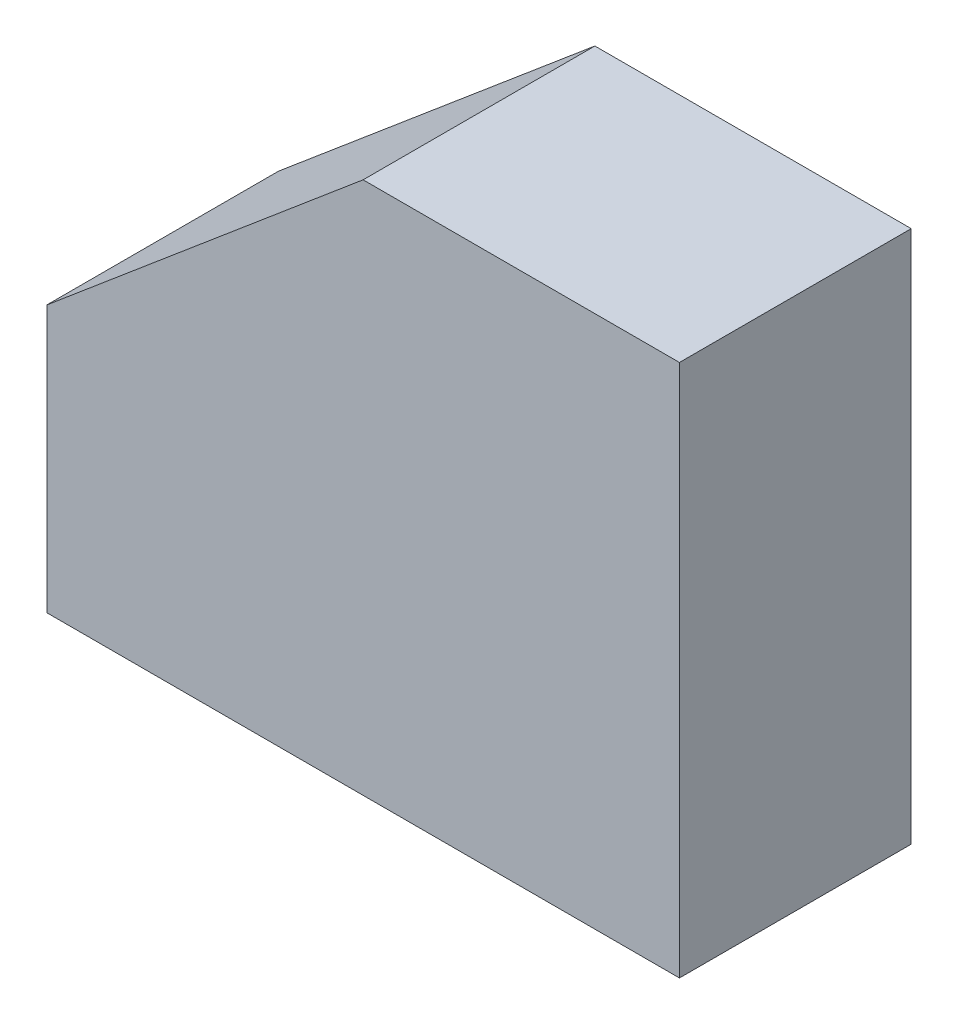
SolidWorks part; units mm, degrees
ref_plane "Front Plane" through (0, 0, 0) normal (0, 0, 1) x (1, 0, 0)
ref_plane "Top Plane" through (0, 0, 0) normal (0, 1, 0) x (1, 0, 0)
ref_plane "Right Plane" through (0, 0, 0) normal (1, 0, 0) x (0, 0, -1)
sketch "Sketch1" plane through (0, 0, 0) normal (0, 0, 1) x (1, 0, 0)
  line L1 (0, 0) -> (13.6485, 0)
  line L2 (0, 0) -> (0, 11.4999)
  line L3 (0, 11.4999) -> (13.6485, 11.4999)
  line L4 (13.6485, 0) -> (13.6485, 11.4999)
  point P4 (13.6485, 11.4999)
extrude "Extrude1" add sketch "Sketch1" along normal mid plane 5
sketch "Sketch2" plane through (0, 0, -2.5) normal (0, 0, -1) x (-1, 0, 0)
  line L0 (-6.8242, 11.4999) -> (0, 5.75)
  line L1 (-13.6485, 11.4999) -> (0, 11.4999) construction
  line L2 (0, 11.4999) -> (0, 0) construction
  line L3 (-6.8242, 11.4999) -> (0, 11.4999)
  line L4 (0, 11.4999) -> (0, 5.75)
extrude "Cut-Extrude1" cut sketch "Sketch2" against normal blind 10
